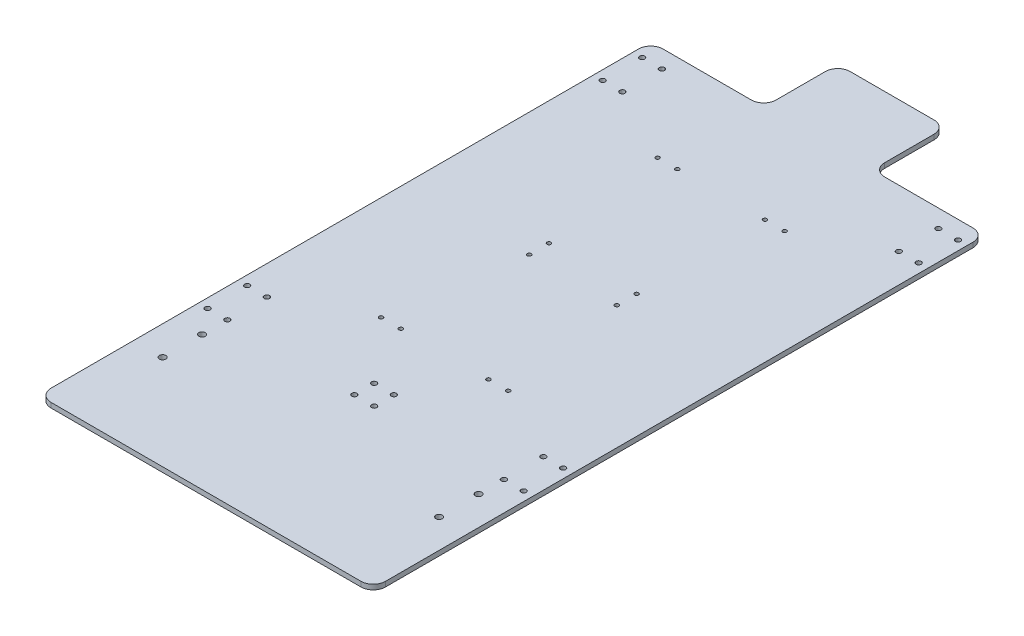
SolidWorks part; units mm, degrees
ref_plane "前视基准面" through (0, 0, 0) normal (0, 0, 1) x (1, 0, 0)
ref_plane "上视基准面" through (0, 0, 0) normal (0, 1, 0) x (1, 0, 0)
ref_plane "右视基准面" through (0, 0, 0) normal (1, 0, 0) x (0, 0, -1)
sketch "草图1" plane through (0, 0, 0) normal (0, 1, 0) x (1, 0, 0)
  line L1 (-135.5, 210.25) -> (135.5, 210.25)
  line L2 (-135.5, 210.25) -> (-135.5, -210.25)
  line L3 (-135.5, -210.25) -> (135.5, -210.25)
  line L4 (135.5, 210.25) -> (135.5, -210.25)
  line L5 (-135.5, 210.25) -> (135.5, -210.25) construction
  line L6 (-135.5, -210.25) -> (135.5, 210.25) construction
  point P0 (0, 0)
  dimension "D1" = 271
  dimension "D2" = 420.5
extrude "凸台-拉伸1" add sketch "草图1" along normal blind 4
sketch "草图2" plane through (0, 4, 0) normal (0, 1, 0) x (1, 0, 0)
  line L0 (0, 0) -> (266.2405, 0) construction
  line L1 (0, 0) -> (0, 278.2504) construction
  line L2 (-135.5, 210.25) -> (135.5, 210.25) construction
  line L3 (135.5, 210.25) -> (135.5, -210.25) construction
  line L4 (-135.5, -210.25) -> (135.5, -210.25) construction
  circle A0 centre (112, 195.75) radius 2.1
  circle A1 centre (128, 195.75) radius 2.1
  circle A2 centre (112, 163.75) radius 2.1
  circle A3 centre (128, 163.75) radius 2.1
  circle A4 centre (-128, 163.75) radius 2.1
  circle A5 centre (-112, 163.75) radius 2.1
  circle A6 centre (-128, 195.75) radius 2.1
  circle A7 centre (-112, 195.75) radius 2.1
  circle A16 centre (128, -124.25) radius 2.1
  circle A17 centre (112, -124.25) radius 2.1
  circle A18 centre (128, -156.25) radius 2.1
  circle A19 centre (112, -156.25) radius 2.1
  circle A20 centre (-112, -156.25) radius 2.1
  circle A21 centre (-128, -156.25) radius 2.1
  circle A22 centre (-112, -124.25) radius 2.1
  circle A23 centre (-128, -124.25) radius 2.1
  dimension "D1" = 4.2
  dimension "D2" = 14.5
  dimension "D3" = 16
  dimension "D4" = 32
  dimension "D5" = 7.5
  dimension "D6" = 16
  dimension "D7" = 32
  dimension "D8" = 4.2
  dimension "D9" = 7.5
  dimension "D10" = 54
extrude "切除-拉伸1" cut sketch "草图2" against normal through all
sketch "草图3" plane through (0, 4, 0) normal (0, 1, 0) x (1, 0, 0)
  line L0 (0, 293.0098) -> (0, 0) construction
  line L5 (-135.5, -215) -> (-135.5, -210.25)
  line L7 (102, -222.75) -> (-102, -222.75)
  line L8 (135.5, -210.25) -> (135.5, -215)
  line L14 (102, -222.75) -> (135.5, -222.75)
  line L19 (-102, -222.75) -> (102, -210.25) construction
  line L20 (-102, -210.25) -> (102, -222.75) construction
  line L23 (0, 0) -> (212.7777, 0) construction
  line L25 (135.5, -210.25) -> (135.5, 210.25) construction
  line L28 (-135.5, -210.25) -> (135.5, -210.25)
  line L29 (135.5, -222.75) -> (135.5, -215)
  line L30 (-102, -222.75) -> (-135.5, -222.75)
  line L36 (-135.5, -222.75) -> (-135.5, -215)
  point P0 (-130.5, -237)
  point P14 (130.5, -237)
  point P15 (0, -216.5)
  dimension "D1" = 222.75
  dimension "D4" = 204
  dimension "D7" = 215
extrude "凸台-拉伸2" add sketch "草图3" against normal up to surface (4 mm away) up to face at (-112, 0, -165.85)
fillet "圆角2" radius 10 2 edges at (135.5, 2, -210.25) (-135.5, 2, -210.25)
sketch "草图7" plane through (0, 0, 0) normal (0, -1, 0) x (1, 0, 0)
  line L0 (0, 0) -> (227.5349, 0) construction
  line L1 (-135.5, -210.25) -> (135.5, 210.25) construction
  line L2 (0, 0) -> (0, 257.0342) construction
  line L3 (-135.5, -210.25) -> (135.5, -210.25) construction
  line L4 (-135.5, -210.25) -> (-135.5, 210.25) construction
  line L6 (-35.5, -11.75) -> (35.5, -27.75) construction
  line L7 (-35.5, -27.75) -> (35.5, -11.75) construction
  circle A0 centre (-51.5, -131.75) radius 1.6
  circle A1 centre (-35.5, -131.75) radius 1.6
  circle A2 centre (35.5, -131.75) radius 1.6
  circle A3 centre (51.5, -131.75) radius 1.6
  circle A4 centre (-51.5, 92.25) radius 1.6
  circle A5 centre (-35.5, 92.25) radius 1.6
  circle A6 centre (35.5, 92.25) radius 1.6
  circle A7 centre (51.5, 92.25) radius 1.6
  circle A8 centre (-35.5, -27.75) radius 1.6
  circle A9 centre (-35.5, -11.75) radius 1.6
  circle A10 centre (35.5, -11.75) radius 1.6
  circle A11 centre (35.5, -27.75) radius 1.6
  point P31 (0, -19.75)
  dimension "D1" = 3.2
  dimension "D2" = 78.5
  dimension "D3" = 84
  dimension "D4" = 16
  dimension "D5" = 3.2
  dimension "D6" = 92.25
  dimension "D7" = 84
  dimension "D8" = 16
  dimension "D9" = 16
  dimension "D10" = 3.2
  dimension "D11" = 100
  dimension "D12" = 182.5
  dimension "D13" = 19.75
extrude "切除-拉伸4" cut sketch "草图7" against normal through all
sketch "草图8" plane through (0, 0, 0) normal (0, -1, 0) x (1, 0, 0)
  line L0 (0, 0) -> (188.6484, 0) construction
  line L1 (0, 0) -> (0, -284.3372) construction
  line L3 (-44, -210.25) -> (44, -210.25)
  line L4 (-44, -210.25) -> (-44, -270.25)
  line L5 (-44, -270.25) -> (44, -270.25)
  line L6 (44, -210.25) -> (44, -270.25)
  line L7 (-44, -210.25) -> (44, -270.25) construction
  line L8 (-44, -270.25) -> (44, -210.25) construction
  point P3 (0, -240.25)
  dimension "D1" = 60
  dimension "D2" = 88
  dimension "D3" = 210.25
extrude "凸台-拉伸3" add sketch "草图8" against normal blind 4
fillet "圆角3" radius 10 2 edges at (44, 2, -270.25) (-44, 2, -270.25)
sketch "草图9" plane through (0, 0, 0) normal (0, -1, 0) x (1, 0, 0)
  line L0 (0, 0) -> (231.0993, 0) construction
  line L1 (0, 0) -> (0, 302.2493) construction
  line L2 (135.5, 222.75) -> (-135.5, 222.75) construction
  circle A0 centre (-8, 157.35) radius 2.1
  circle A1 centre (8, 157.35) radius 2.1
  circle A2 centre (-8, 141.35) radius 2.1
  circle A3 centre (8, 141.35) radius 2.1
  dimension "D1" = 16
  dimension "D2" = 4.2
  dimension "D3" = 16
  dimension "D4" = 65.4
extrude "切除-拉伸5" cut sketch "草图9" against normal through all
sketch "草图10" plane through (0, 0, 0) normal (0, -1, 0) x (1, 0, 0)
  line L0 (0, 0) -> (0, 222.75) construction
  line L1 (135.5, 222.75) -> (-135.5, 222.75) construction
  circle A0 centre (-112, 208.75) radius 2.6
  circle A1 centre (-112, 176.75) radius 2.6
  circle A2 centre (112, 176.75) radius 2.6
  circle A3 centre (112, 208.75) radius 2.6
  circle A4 centre (-112, 156.25) radius 2.1 construction
  dimension "D1" = 5.2
  dimension "D3" = 20.5
  dimension "D2" = 32
  dimension "D4" = 112
extrude "切除-拉伸6" cut sketch "草图10" against normal blind 4
sketch "草图12" plane through (0, 0, 0) normal (0, -1, 0) x (1, 0, 0)
  line L1 (135.5, 222.75) -> (-135.5, 222.75)
  line L2 (135.5, 222.75) -> (135.5, 285.5784)
  line L3 (135.5, 285.5784) -> (-135.5, 285.5784)
  line L4 (-135.5, 222.75) -> (-135.5, 285.5784)
  dimension "D1" = 62.8284
  dimension "D2" = 271
extrude "凸台-拉伸4" add sketch "草图12" against normal blind 4
fillet "圆角4" radius 10 4 edges at (44, 2, -210.25) (-135.5, 2, 285.5784) (-44, 2, -210.25) (135.5, 2, 285.5784)
